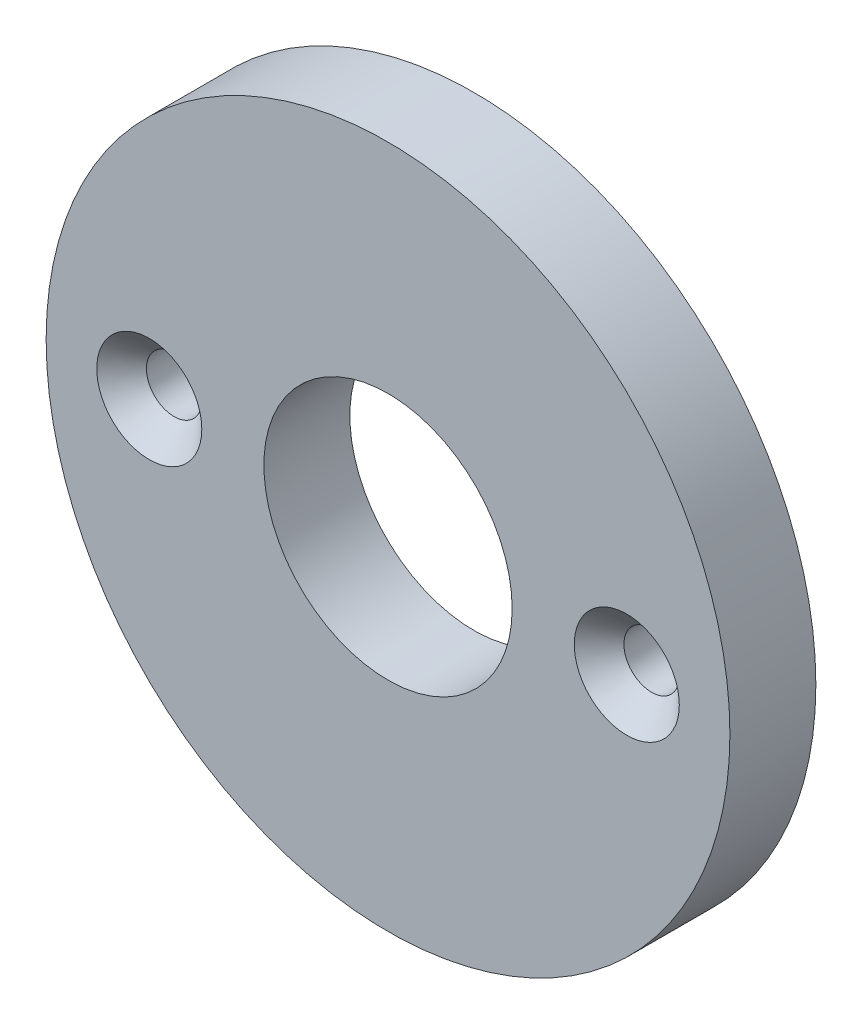
SolidWorks part; units mm, degrees
ref_plane "Front Plane" through (0, 0, 0) normal (0, 0, 1) x (1, 0, 0)
ref_plane "Top Plane" through (0, 0, 0) normal (0, 1, 0) x (1, 0, 0)
ref_plane "Right Plane" through (0, 0, 0) normal (1, 0, 0) x (0, 0, -1)
sketch "Sketch1" plane through (0, 0, 0) normal (0, 0, 1) x (1, 0, 0)
  circle A0 centre (0, 0) radius 6.5
  circle A1 centre (0, 0) radius 17.9
  dimension "D1" = 13
  dimension "D2" = 35.8
extrude "Boss-Extrude1" add sketch "Sketch1" along normal blind 4.5
sketch "Sketch2" plane through (0, 0, 4.5) normal (0, 0, 1) x (1, 0, 0)
  line L0 (12.5, 0) -> (-12.5, 0) construction
  point P0 (-12.5, 0)
  point P6 (0, 0)
  point P8 (12.5, 0)
  dimension "D1" = 25
hole_wizard "CSK for M2.5 Flat Head Machine Screw2" positions "Sketch5" profile "Sketch6" countersink size "M2.5" standard "ANSI Metric"
sketch "Sketch5" plane through (0, 0, 4.5) normal (0, 0, 1) x (1, 0, 0)
  point P0 (-12.5, 0)
  point P3 (12.5, 0)
sketch "Sketch6" plane through (-12.5, 0, 4.5) normal (1, 0, 0) x (0, -1, 0)
  line L0 (0, 0) -> (0, 5.3712)
  line L1 (0, 5.3712) -> (1.45, 4.5)
  line L2 (1.45, 4.5) -> (1.45, 1.3)
  line L3 (1.45, 1.3) -> (2.75, 0)
  line L5 (2.75, 0) -> (0, 0)
  line L6 (-1.45, 1.3) -> (-2.75, 0) construction
  line L10 (0, 5.3712) -> (-1.45, 4.5) construction
  line L11 (0, -6.35) -> (0, 107.95) construction
  dimension "Hole Dia." = 2.9
  dimension "Hole Depth" = 4.5
  dimension "Near C'Sink Dia." = 5.5
  dimension "Near C'Sink Angle" = 90
  dimension "Drill Angle" = 118
